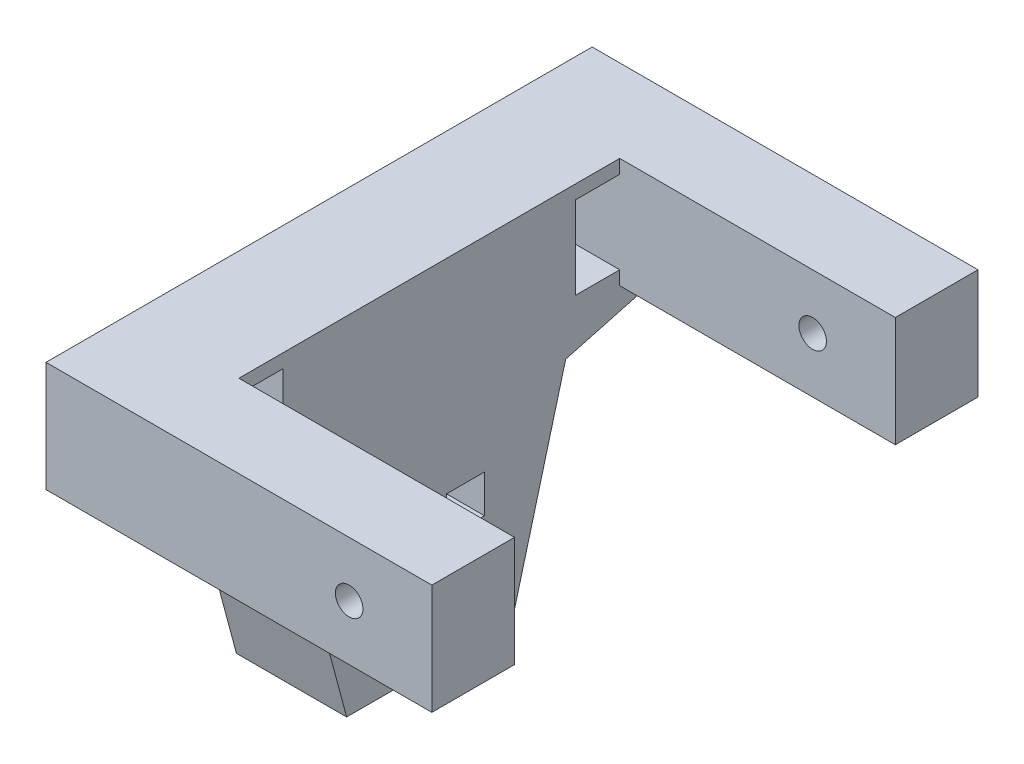
SolidWorks part; units mm, degrees
ref_plane "Front Plane" through (0, 0, 0) normal (0, 0, 1) x (1, 0, 0)
ref_plane "Top Plane" through (0, 0, 0) normal (0, 1, 0) x (1, 0, 0)
ref_plane "Right Plane" through (0, 0, 0) normal (1, 0, 0) x (0, 0, -1)
sketch "Sketch1" plane through (0, 0, 0) normal (1, 0, 0) x (0, 0, -1)
  line L5 (15, 0) -> (-15, 0)
  line L12 (-49.545, 63) -> (49.545, 63)
  line L13 (-49.545, 31.5) -> (-15, 0)
  line L14 (49.545, 31.5) -> (15, 0)
  line L15 (-49.545, 63) -> (-49.545, 31.5)
  line L16 (49.545, 63) -> (49.545, 31.5)
  point P3 (0, 0)
  point P11 (0, 0)
  dimension "D1" = 31.5
  dimension "D2" = 63
  dimension "D3" = 30
  dimension "D4" = 34.545
  dimension "D5" = 31.5
  dimension "D6" = 34.545
extrude "Boss-Extrude1" add sketch "Sketch1" along normal blind 20 contours L5 L13 L15 L12 L16 L14
sketch "Sketch3" plane through (20, 0, 0) normal (1, 0, 0) x (0, 0, -1)
  line L0 (-10, 12.875) -> (-10, 6)
  line L1 (-10, 26) -> (-3.125, 26)
  line L2 (-10, 26) -> (-10, 19.125)
  line L3 (-10, 6) -> (-3.125, 6)
  line L4 (-8, 12.875) -> (-8, 12)
  line L5 (-10, 19.125) -> (-8, 19.125)
  line L6 (-10, 12.875) -> (-8, 12.875)
  line L7 (-3.125, 26) -> (-3.125, 24)
  line L8 (-3.125, 6) -> (-3.125, 8)
  line L9 (-8, 20) -> (-6, 20)
  line L10 (-8, 12) -> (-6, 12)
  line L11 (-6, 20) -> (-6, 12)
  line L12 (-8, 19.125) -> (-8, 20)
  line L13 (-3.125, 24) -> (-4, 24)
  line L14 (-4, 24) -> (-4, 22)
  line L15 (-3.125, 8) -> (-4, 8)
  line L16 (-4, 8) -> (-4, 10)
  line L17 (-4, 10) -> (4, 10)
  line L18 (-4, 22) -> (4, 22)
  line L19 (4, 8) -> (4, 10)
  line L20 (3.125, 8) -> (4, 8)
  line L21 (4, 24) -> (4, 22)
  line L22 (3.125, 24) -> (4, 24)
  line L23 (8, 19.125) -> (8, 20)
  line L24 (6, 20) -> (6, 12)
  line L25 (8, 12) -> (6, 12)
  line L26 (8, 20) -> (6, 20)
  line L27 (3.125, 6) -> (3.125, 8)
  line L28 (3.125, 26) -> (3.125, 24)
  line L29 (10, 12.875) -> (8, 12.875)
  line L30 (10, 19.125) -> (8, 19.125)
  line L31 (8, 12.875) -> (8, 12)
  line L32 (10, 6) -> (3.125, 6)
  line L33 (10, 26) -> (10, 19.125)
  line L34 (10, 26) -> (3.125, 26)
  line L35 (10, 12.875) -> (10, 6)
  line L36 (15, 0) -> (-15, 0) construction
  point P13 (0, 10)
  point P14 (0, 22)
  dimension "D1" = 6.25
  dimension "D2" = 2
  dimension "D3" = 8
  dimension "D4" = 2
  dimension "D5" = 2
  dimension "D6" = 4
  dimension "D7" = 0.875
  dimension "D8" = 2
  dimension "D9" = 4
  dimension "D10" = 10
  dimension "D11" = 8
  dimension "D12" = 6.875
  dimension "D13" = 6.875
  dimension "D14" = 6.875
  dimension "D15" = 6.875
  dimension "D16" = 2
  dimension "D17" = 2
  dimension "D18" = 6.875
  dimension "D19" = 6.875
  dimension "D20" = 2
  dimension "D21" = 2
  dimension "D22" = 2
  dimension "D23" = 2
  dimension "D24" = 2
  dimension "D25" = 0.875
  dimension "D26" = 0.875
  dimension "D27" = 0.875
  dimension "D28" = 0.875
extrude "Cut-Extrude1" cut sketch "Sketch3" against normal blind 20
sketch "Sketch4" plane through (20, 0, 0) normal (1, 0, 0) x (0, 0, -1)
  line L0 (-3.125, 26) -> (-10, 26) construction
  line L1 (-49.545, 63) -> (-34.545, 63)
  line L2 (-49.545, 63) -> (-49.545, 43)
  line L3 (-49.545, 43) -> (-34.545, 43)
  line L4 (-34.545, 63) -> (-34.545, 43)
  line L5 (34.5408, 63) -> (49.5408, 63)
  line L6 (34.5408, 63) -> (34.5408, 43)
  line L7 (34.5408, 43) -> (49.5408, 43)
  line L8 (49.5408, 63) -> (49.5408, 43)
  line L11 (-49.545, 31.5) -> (-49.545, 63) construction
  point P8 (-49.2037, 77.4433)
  point P9 (-34.545, 53)
  point P12 (-34.0491, 63)
  dimension "D1" = 69.0858
  dimension "D2" = 15
  dimension "D3" = 15
  dimension "D4" = 20
  dimension "D5" = 20
  dimension "D6" = 27
extrude "Boss-Extrude2" add sketch "Sketch4" along normal blind 50
sketch "Sketch5" plane through (0, 0, 49.545) normal (0, 0, 1) x (1, 0, 0)
  line L0 (70, 63) -> (70, 43) construction
  circle A0 centre (55, 53) radius 2.5
  point P4 (70, 53)
  dimension "D1" = 5
  dimension "D2" = 15
extrude "Cut-Extrude2" cut sketch "Sketch5" against normal through all
sketch "Sketch6" plane through (20, 0, 0) normal (1, 0, 0) x (0, 0, -1)
  line L1 (-34.545, 60.5) -> (-26.545, 60.5)
  line L2 (-34.545, 60.5) -> (-34.545, 45.5)
  line L3 (-34.545, 45.5) -> (-26.545, 45.5)
  line L4 (-26.545, 60.5) -> (-26.545, 45.5)
  line L5 (34.5408, 63) -> (34.5408, 43) construction
  line L6 (34.5408, 60.5) -> (26.5408, 60.5)
  line L7 (34.5408, 60.5) -> (34.5408, 45.5)
  line L8 (34.5408, 45.5) -> (26.5408, 45.5)
  line L9 (26.5408, 60.5) -> (26.5408, 45.5)
  line L10 (-34.545, 43) -> (-34.545, 63) construction
  line L11 (-34.545, 43) -> (-34.545, 63) construction
  point P12 (-34.545, 53)
  point P13 (-26.545, 53)
  point P14 (-6.0486, 45.5)
  dimension "D1" = 8
  dimension "D2" = 8
  dimension "D3" = 15
  dimension "D4" = 15
extrude "Cut-Extrude3" cut sketch "Sketch6" against normal through all
sketch "Sketch7" plane through (20, 0, 0) normal (1, 0, 0) x (0, 0, -1)
  line L0 (-49.545, 43) -> (-24.741, 36.3538)
  line L1 (-24.741, 36.3538) -> (-15, 0)
  line L2 (49.5408, 43) -> (24.741, 36.3538)
  line L3 (24.741, 36.3538) -> (15, 0)
  line L5 (-10, 12.875) -> (-10, 6) construction
  line L6 (10, 19.125) -> (10, 26) construction
  line L7 (-49.545, 43) -> (-34.545, 43) construction
  line L8 (34.5408, 43) -> (49.5408, 43) construction
  line L9 (-49.545, 43) -> (-52.7748, 23.3551)
  line L10 (-52.7748, 23.3551) -> (-15, 0)
  line L11 (49.5408, 43) -> (56.1932, 18.1769)
  line L12 (56.1932, 18.1769) -> (15, 0)
  dimension "D1" = 15
  dimension "D2" = 15
  dimension "D3" = 15
  dimension "D4" = 15.002
extrude "Cut-Extrude4" cut sketch "Sketch7" against normal through all
